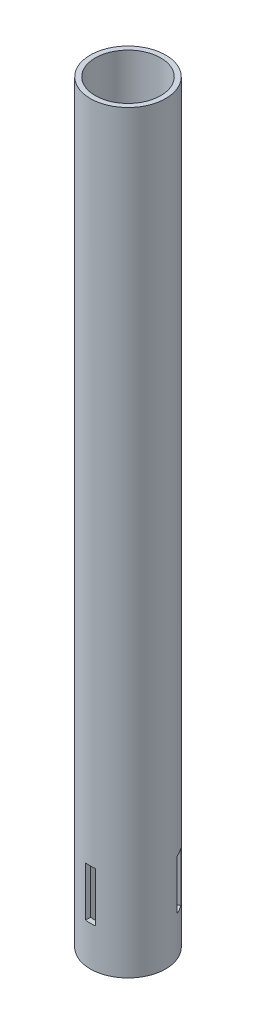
SolidWorks part; units mm, degrees
ref_plane "Front Plane" through (0, 0, 0) normal (0, 0, 1) x (1, 0, 0)
ref_plane "Top Plane" through (0, 0, 0) normal (0, 1, 0) x (1, 0, 0)
ref_plane "Right Plane" through (0, 0, 0) normal (1, 0, 0) x (0, 0, -1)
sketch "Sketch1" plane through (0, 0, 0) normal (0, 1, 0) x (1, 0, 0)
  circle A0 centre (0, 0) radius 3.8
  circle A1 centre (0, 0) radius 3.3
  dimension "D1" = 7.6
  dimension "D2" = 0.5
extrude "Boss-Extrude2" add sketch "Sketch1" along normal blind 76 contours A1
sketch "Sketch2" plane through (0, 0, 0) normal (0, 0, 1) x (1, 0, 0)
  line L0 (0, 0) -> (0, 20.4478)
  line L1 (0.55, 0) -> (-0.55, 0) construction
  line L2 (-0.5, 4) -> (0.5, 4)
  line L3 (-0.5, 4) -> (-0.5, 9)
  line L4 (-0.5, 9) -> (0.5, 9)
  line L5 (0.5, 4) -> (0.5, 9)
  line L6 (-0.5, 4) -> (0.5, 9) construction
  line L7 (-0.5, 9) -> (0.5, 4) construction
  point P3 (0, 6.5)
  dimension "D1" = 5
  dimension "D2" = 1
  dimension "D3" = 4
extrude "Cut-Extrude4" cut sketch "Sketch2" along normal blind 8 contours L5 L4 L3 L2
pattern_circular "CirPattern1" count 3 over 360 about axis through (0, 0, 0) along (0, 1, 0) of "Cut-Extrude4"
scale "Scale2" scale about origin uniform scaling yes scale factor 10
